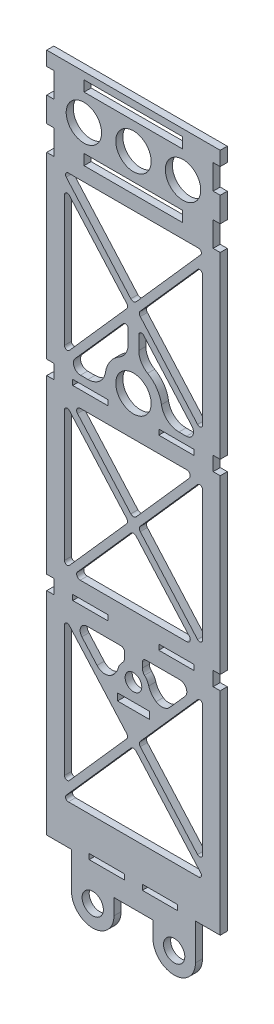
SolidWorks part; units mm, degrees
ref_plane "前视基准面" through (0, 0, 0) normal (0, 0, 1) x (1, 0, 0)
ref_plane "上视基准面" through (0, 0, 0) normal (0, 1, 0) x (1, 0, 0)
ref_plane "右视基准面" through (0, 0, 0) normal (1, 0, 0) x (0, 0, -1)
other "Configuration Table"
sketch "草图2" plane through (0, 0, 0) normal (0, 0, 1) x (1, 0, 0)
  line L0 (-24.5, 104.1197) -> (-24.5, 100.1197)
  line L1 (-24.5, 91.6197) -> (-24.5, 86.1197)
  line L2 (-24.5, 79.1197) -> (-24.5, 30.0197)
  line L3 (-24.5, 23.0197) -> (-24.5, -6.8494)
  line L4 (24.5, 104.1197) -> (24.5, 100.1197)
  line L5 (24.5, 93.1197) -> (24.5, 86.1197)
  line L6 (24.5, 79.1197) -> (24.5, 28.5197)
  line L7 (24.5, 24.5197) -> (24.5, -18.6345)
  line L8 (-13.9612, 101.1197) -> (-13.9612, 99.1197)
  line L9 (-13.9612, 99.1197) -> (13.9189, 99.1197)
  line L10 (13.9189, 101.1197) -> (13.9189, 99.1197)
  line L11 (0, 84.1197) -> (-13.9612, 84.1197)
  line L12 (0, 84.1197) -> (13.9189, 84.1197)
  line L13 (-13.9612, 84.1197) -> (-13.9612, 81.1197)
  line L14 (-13.9612, 81.1197) -> (13.9189, 81.1197)
  line L15 (13.9189, 84.1197) -> (13.9189, 81.1197)
  line L16 (0, 77.1197) -> (-18.3888, 77.1197)
  line L17 (0, 77.1197) -> (18.3888, 77.1197)
  line L18 (-24.5, -6.8494) -> (-24.5, -24.0803)
  line L19 (-24.5, -28.0803) -> (-24.5, -53.8803)
  line L20 (24.5, -18.6345) -> (24.5, -24.0803)
  line L21 (24.5, -28.0803) -> (24.5, -53.8803)
  line L22 (-24.5, -53.8803) -> (-24.5, -87.8803)
  line L23 (24.5, -53.8803) -> (24.5, -87.8803)
  line L24 (24.5, 104.1197) -> (-24.5, 104.1197)
  line L25 (-13.9612, 101.1197) -> (-13.9612, 102.1197)
  line L26 (-13.9612, 102.1197) -> (13.9189, 102.1197)
  line L27 (13.9189, 101.1197) -> (13.9189, 102.1197)
  line L28 (-24.5, -87.8803) -> (-17.5, -87.8803)
  line L29 (17.5, -87.8803) -> (24.5, -87.8803)
  line L30 (14.955, 29.3897) -> (12.8452, 29.3897)
  line L31 (-12.8452, 29.3897) -> (-14.955, 29.3897)
  line L32 (-24.5, 100.1197) -> (-22.5, 100.1197)
  line L33 (-22.5, 100.1197) -> (-22.5, 93.1197)
  line L34 (0.7489, 55.1752) -> (18.9879, 75.7895)
  line L35 (-16.4529, 32.7149) -> (-3.7447, 47.0782)
  line L36 (-0.7489, 55.1752) -> (-18.9879, 75.7895)
  line L37 (16.4529, 32.7149) -> (3.7447, 47.0782)
  line L38 (-3.7447, 47.0782) -> (-2.8992, 48.0338)
  line L39 (3.7447, 47.0782) -> (2.8992, 48.0338)
  line L40 (-7.1582, 25.7697) -> (-7.1582, 26.5197)
  line L41 (-7.1582, 26.5197) -> (-7.1582, 27.2697)
  line L42 (-17.1582, 27.2697) -> (-17.1582, 25.7697)
  line L43 (-7.1582, 27.2697) -> (-17.1582, 27.2697)
  line L44 (-7.1582, 25.7697) -> (-17.1582, 25.7697)
  line L45 (-22.5, 93.1197) -> (-24.5, 93.1197)
  line L46 (-24.5, 93.1197) -> (-24.5, 91.6197)
  line L47 (-22.5, 86.1197) -> (-24.5, 86.1197)
  line L48 (-22.5, 86.1197) -> (-22.5, 79.1197)
  line L49 (-22.5, 79.1197) -> (-24.5, 79.1197)
  line L50 (24.5, 100.1197) -> (22.5, 100.1197)
  line L51 (22.5, 100.1197) -> (22.5, 93.1197)
  line L52 (22.5, 93.1197) -> (24.5, 93.1197)
  line L53 (22.5, 86.1197) -> (24.5, 86.1197)
  line L54 (22.5, 86.1197) -> (22.5, 79.1197)
  line L55 (22.5, 79.1197) -> (24.5, 79.1197)
  line L56 (7.1582, 25.7697) -> (7.1582, 26.5197)
  line L57 (7.1582, 26.5197) -> (7.1582, 27.2697)
  line L58 (17.1582, 27.2697) -> (17.1582, 25.7697)
  line L59 (7.1582, 27.2697) -> (17.1582, 27.2697)
  line L60 (7.1582, 25.7697) -> (17.1582, 25.7697)
  line L61 (-18.1008, 19.1687) -> (-1.9215, 0.8823)
  line L62 (0.7489, -2.1359) -> (15.7901, -19.1359)
  line L63 (-15.7901, 19.5752) -> (-3.7447, 5.9611)
  line L64 (1.9215, -0.443) -> (18.1008, -18.7294)
  line L65 (18.1008, 19.1687) -> (1.9215, 0.8823)
  line L66 (-0.7489, -2.1359) -> (-15.7901, -19.1359)
  line L67 (15.7901, 19.5752) -> (3.7447, 5.9611)
  line L68 (-1.9215, -0.443) -> (-18.1008, -18.7294)
  line L69 (-3.7447, 5.9611) -> (-2.8992, 5.0055)
  line L70 (3.7447, 5.9611) -> (2.8992, 5.0055)
  line L71 (-2.8992, 5.0055) -> (-0.7489, 2.5752)
  line L72 (0.7489, 2.5752) -> (2.8992, 5.0055)
  line L73 (-7.1582, -26.8303) -> (-7.1582, -26.0803)
  line L74 (-7.1582, -26.0803) -> (-7.1582, -25.3303)
  line L75 (-17.1582, -25.3303) -> (-17.1582, -26.8303)
  line L76 (-7.1582, -25.3303) -> (-17.1582, -25.3303)
  line L77 (-7.1582, -26.8303) -> (-17.1582, -26.8303)
  line L78 (7.1582, -26.8303) -> (7.1582, -26.0803)
  line L79 (7.1582, -26.0803) -> (7.1582, -25.3303)
  line L80 (17.1582, -25.3303) -> (17.1582, -26.8303)
  line L81 (7.1582, -25.3303) -> (17.1582, -25.3303)
  line L82 (7.1582, -26.8303) -> (17.1582, -26.8303)
  line L83 (0, -76.6803) -> (-18.3888, -76.6803)
  line L84 (0, -76.6803) -> (18.3888, -76.6803)
  line L85 (-18.1008, -33.4313) -> (-1.9215, -51.7177)
  line L86 (0.7489, -54.7359) -> (18.9879, -75.3502)
  line L87 (1.9215, -53.043) -> (18.1008, -71.3294)
  line L88 (18.1008, -33.4313) -> (1.9215, -51.7177)
  line L89 (-0.7489, -54.7359) -> (-18.9879, -75.3502)
  line L90 (-1.9215, -53.043) -> (-18.1008, -71.3294)
  line L91 (-19.5, -11.0803) -> (-19.5, -18.1993)
  line L92 (-19.5, -11.0803) -> (-19.5, 18.6386)
  line L93 (-2.6704, 0.2197) -> (2.6704, 0.2197)
  line L94 (0, -2.7986) -> (0, 3.2379)
  line L95 (19.5, 18.6386) -> (19.5, -18.1993)
  line L96 (-19.5, -41.0803) -> (-19.5, -33.9614)
  line L97 (-19.5, -41.0803) -> (-19.5, -70.7993)
  line L98 (19.5, -70.7993) -> (19.5, -33.9614)
  line L99 (-22.5, 28.5197) -> (-22.5, 24.5197)
  line L100 (-22.5, 28.5197) -> (-24.5, 28.5197)
  line L101 (-24.5, 30.0197) -> (-24.5, 28.5197)
  line L102 (-22.5, 24.5197) -> (-24.5, 24.5197)
  line L103 (-24.5, 23.0197) -> (-24.5, 24.5197)
  line L104 (22.5, 28.5197) -> (22.5, 24.5197)
  line L105 (22.5, 28.5197) -> (24.5, 28.5197)
  line L106 (22.5, 24.5197) -> (24.5, 24.5197)
  line L107 (-22.5, -28.0803) -> (-22.5, -24.0803)
  line L108 (-22.5, -28.0803) -> (-24.5, -28.0803)
  line L109 (-22.5, -24.0803) -> (-24.5, -24.0803)
  line L110 (22.5, -28.0803) -> (22.5, -24.0803)
  line L111 (22.5, -28.0803) -> (24.5, -28.0803)
  line L112 (22.5, -24.0803) -> (24.5, -24.0803)
  line L113 (-2.5, -87.8803) -> (-2.5, -87.1303)
  line L114 (-2.5, -87.1303) -> (-2.5, -86.3803)
  line L115 (-12.5, -86.3803) -> (-12.5, -87.8803)
  line L116 (-2.5, -86.3803) -> (-12.5, -86.3803)
  line L117 (-2.5, -87.8803) -> (-12.5, -87.8803)
  line L118 (2.5, -87.8803) -> (2.5, -87.1303)
  line L119 (12.5, -86.3803) -> (12.5, -87.8803)
  line L120 (2.5, -86.3803) -> (12.5, -86.3803)
  line L121 (2.5, -87.8803) -> (12.5, -87.8803)
  line L122 (2.5, -86.3803) -> (2.5, -87.1303)
  line L123 (-18.1008, 71.7687) -> (-1.9215, 53.4823)
  line L124 (1.9215, 52.157) -> (18.1008, 33.8706)
  line L125 (18.1008, 71.7687) -> (1.9215, 53.4823)
  line L126 (-1.9215, 52.157) -> (-18.1008, 33.8706)
  line L127 (-19.5, 41.5197) -> (-19.5, 34.4007)
  line L128 (-19.5, 41.5197) -> (-19.5, 71.2386)
  line L129 (19.5, 71.2386) -> (19.5, 34.4007)
  line L130 (17.5, -87.8803) -> (17.5, -98.1197)
  line L131 (5.5, -93.6397) -> (5.5, -98.1197)
  line L132 (5.5, -93.6397) -> (0, -93.6397)
  line L133 (-17.5, -87.8803) -> (-17.5, -98.1197)
  line L134 (-5.5, -93.6397) -> (-5.5, -98.1197)
  line L135 (-5.5, -93.6397) -> (0, -93.6397)
  line L136 (-1.5, 47.5037) -> (-1.5, 43.648)
  line L137 (1.5, 47.5037) -> (1.5, 43.648)
  line L138 (0, 21.2379) -> (-15.0412, 21.2379)
  line L139 (0, 21.2379) -> (15.0412, 21.2379)
  line L140 (0, -20.7986) -> (-15.0412, -20.7986)
  line L141 (0, -20.7986) -> (15.0412, -20.7986)
  line L142 (-14.5683, -34.4056) -> (-10.2837, -39.2483)
  line L143 (14.5683, -34.4056) -> (10.2837, -39.2483)
  line L144 (3.5, -31.0803) -> (13.0705, -31.0803)
  line L145 (-3.5, -31.0803) -> (-13.0705, -31.0803)
  line L147 (2.5, -33.5406) -> (2.5, -32.0803)
  line L148 (-2.5, -33.5406) -> (-2.5, -32.0803)
  line L149 (0, -43.081) -> (-4.5, -43.081)
  line L150 (-4.5, -43.081) -> (-4.5, -45.081)
  line L151 (0, -43.081) -> (4.5, -43.081)
  line L152 (4.5, -43.081) -> (4.5, -45.081)
  line L153 (-4.5, -45.081) -> (4.5, -45.081)
  circle A0 centre (0, 91.6197) radius 5
  circle A1 centre (14, 91.6197) radius 5
  circle A2 centre (-14, 91.6197) radius 5
  arc A3 (14.955, 29.3897) -> (16.4529, 32.7149) centre (14.955, 31.3897) ccw
  arc A4 (-16.4529, 32.7149) -> (-14.955, 29.3897) centre (-14.955, 31.3897) ccw
  arc A5 (-0.7489, 55.1752) -> (0.7489, 55.1752) centre (0, 55.8379) ccw
  arc A6 (-1.5, 47.5037) -> (-2.8992, 48.0338) centre (-2.3, 47.5037) ccw
  arc A7 (2.8992, 48.0338) -> (1.5, 47.5037) centre (2.3, 47.5037) ccw
  arc A8 (-18.3888, 77.1197) -> (-18.9879, 75.7895) centre (-18.3888, 76.3197) ccw
  arc A9 (18.9879, 75.7895) -> (18.3888, 77.1197) centre (18.3888, 76.3197) ccw
  arc A10 (-18.1008, 19.1687) -> (-19.5, 18.6386) centre (-18.7, 18.6386) ccw
  arc A11 (-1.9215, -0.443) -> (-1.9215, 0.8823) centre (-2.6704, 0.2197) ccw
  arc A12 (-0.7489, 2.5752) -> (0.7489, 2.5752) centre (0, 3.2379) ccw
  arc A13 (1.9215, 0.8823) -> (1.9215, -0.443) centre (2.6704, 0.2197) ccw
  arc A14 (0.7489, -2.1359) -> (-0.7489, -2.1359) centre (0, -2.7986) ccw
  arc A15 (-1.9215, -53.043) -> (-1.9215, -51.7177) centre (-2.6704, -52.3803) ccw
  arc A16 (1.9215, -51.7177) -> (1.9215, -53.043) centre (2.6704, -52.3803) ccw
  arc A17 (-18.9879, -75.3502) -> (-18.3888, -76.6803) centre (-18.3888, -75.8803) ccw
  arc A18 (18.3888, -76.6803) -> (18.9879, -75.3502) centre (18.3888, -75.8803) ccw
  arc A19 (0.7489, -54.7359) -> (-0.7489, -54.7359) centre (0, -55.3986) ccw
  arc A20 (-19.5, -18.1993) -> (-18.1008, -18.7294) centre (-18.7, -18.1993) ccw
  arc A21 (19.5, 18.6386) -> (18.1008, 19.1687) centre (18.7, 18.6386) ccw
  arc A22 (18.1008, -18.7294) -> (19.5, -18.1993) centre (18.7, -18.1993) ccw
  arc A23 (-19.5, -70.7993) -> (-18.1008, -71.3294) centre (-18.7, -70.7993) ccw
  arc A24 (-18.1008, -33.4313) -> (-19.5, -33.9614) centre (-18.7, -33.9614) ccw
  arc A25 (18.1008, -71.3294) -> (19.5, -70.7993) centre (18.7, -70.7993) ccw
  arc A26 (19.5, -33.9614) -> (18.1008, -33.4313) centre (18.7, -33.9614) ccw
  arc A27 (-18.1008, 71.7687) -> (-19.5, 71.2386) centre (-18.7, 71.2386) ccw
  arc A28 (-1.9215, 52.157) -> (-1.9215, 53.4823) centre (-2.6704, 52.8197) ccw
  arc A29 (1.9215, 53.4823) -> (1.9215, 52.157) centre (2.6704, 52.8197) ccw
  arc A30 (-19.5, 34.4007) -> (-18.1008, 33.8706) centre (-18.7, 34.4007) ccw
  arc A31 (19.5, 71.2386) -> (18.1008, 71.7687) centre (18.7, 71.2386) ccw
  arc A32 (18.1008, 33.8706) -> (19.5, 34.4007) centre (18.7, 34.4007) ccw
  circle A33 centre (0, 32.3897) radius 5
  arc A34 (7.9048, 33.6204) -> (4, 39.3179) centre (0, 32.3897) ccw
  arc A35 (-4, 39.3179) -> (-7.9048, 33.6204) centre (0, 32.3897) ccw
  arc A36 (-4, 39.3179) -> (-1.5, 43.648) centre (-6.5, 43.648) ccw
  arc A37 (-12.8452, 29.3897) -> (-7.9048, 33.6204) centre (-12.8452, 34.3897) ccw
  arc A38 (7.9048, 33.6204) -> (12.8452, 29.3897) centre (12.8452, 34.3897) ccw
  arc A39 (1.5, 43.648) -> (4, 39.3179) centre (6.5, 43.648) ccw
  arc A40 (5.5, -98.1197) -> (17.5, -98.1197) centre (11.5, -98.1197) ccw
  circle A41 centre (11.5, -98.1197) radius 3
  arc A42 (-17.5, -98.1197) -> (-5.5, -98.1197) centre (-11.5, -98.1197) ccw
  circle A43 centre (-11.5, -98.1197) radius 3
  arc A44 (-15.0412, 21.2379) -> (-15.7901, 19.5752) centre (-15.0412, 20.2379) ccw
  arc A45 (15.7901, 19.5752) -> (15.0412, 21.2379) centre (15.0412, 20.2379) ccw
  arc A46 (-15.7901, -19.1359) -> (-15.0412, -20.7986) centre (-15.0412, -19.7986) ccw
  arc A47 (15.0412, -20.7986) -> (15.7901, -19.1359) centre (15.0412, -19.7986) ccw
  circle A48 centre (0, -38.231) radius 2.35
  arc A49 (-13.0705, -31.0803) -> (-14.5683, -34.4056) centre (-13.0705, -33.0803) ccw
  arc A50 (-3.1154, -34.9838) -> (-4.3214, -36.9757) centre (0, -38.231) ccw
  arc A51 (-3.1154, -34.9838) -> (-2.5, -33.5406) centre (-4.5, -33.5406) ccw
  arc A52 (-6.4077, -39.7795) -> (-4.3214, -36.9757) centre (-9.1229, -35.581) ccw
  arc A53 (-10.2837, -39.2483) -> (-6.4077, -39.7795) centre (-8.0368, -37.2604) ccw
  arc A54 (4.3214, -36.9757) -> (3.1154, -34.9838) centre (0, -38.231) ccw
  arc A55 (-2.5, -32.0803) -> (-3.5, -31.0803) centre (-3.5, -32.0803) ccw
  arc A56 (4.3214, -36.9757) -> (6.4077, -39.7795) centre (9.1229, -35.581) ccw
  arc A57 (6.4077, -39.7795) -> (10.2837, -39.2483) centre (8.0368, -37.2604) ccw
  arc A58 (2.5, -33.5406) -> (3.1154, -34.9838) centre (4.5, -33.5406) ccw
  arc A59 (3.5, -31.0803) -> (2.5, -32.0803) centre (3.5, -32.0803) ccw
  arc A60 (14.5683, -34.4056) -> (13.0705, -31.0803) centre (13.0705, -33.0803) ccw
extrude "凸台-拉伸1" add sketch "草图2" along normal blind 2 contours L133 A42 L134 L135 L132 L131 A40 L130 L29 L23 L21 L111 L110 L112 L20 L7 L106 L104 L105 L6 L55 L54 L53 L5 L52 L51 L50 L4 L24 L0 L32 L33 L45 L46 L1 L47 L48 L49 L2 L101 L100 L99 L102 L103 L3 L18 L109 L107 L108 L19 L22
